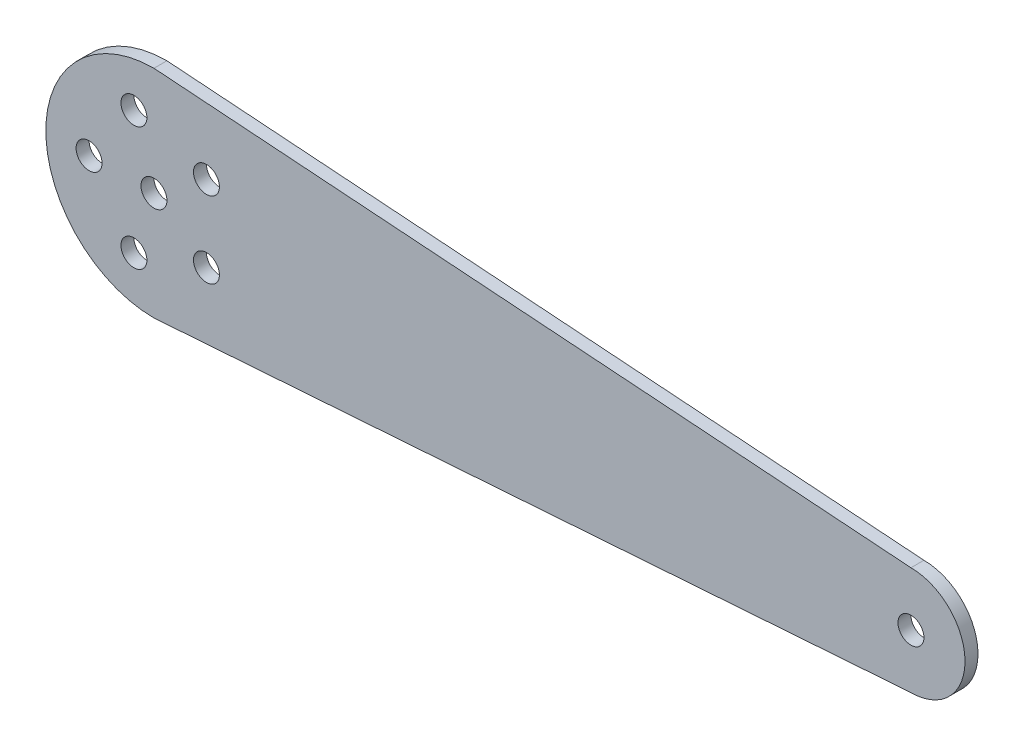
SolidWorks part; units mm, degrees
ref_plane "Front Plane" through (0, 0, 0) normal (0, 0, 1) x (1, 0, 0)
ref_plane "Top Plane" through (0, 0, 0) normal (0, 1, 0) x (1, 0, 0)
ref_plane "Right Plane" through (0, 0, 0) normal (1, 0, 0) x (0, 0, -1)
sketch "Sketch4" plane through (0, 0, 0) normal (0, 0, 1) x (1, 0, 0)
  line L0 (0, 0) -> (175, 0) construction
  line L1 (0, 25) -> (175, 12.5)
  line L2 (0, -25) -> (175, -12.5)
  arc A0 (175, -12.5) -> (175, 12.5) centre (175, 0) ccw
  arc A1 (0, 25) -> (0, -25) centre (0, 0) ccw
  circle A2 centre (0, 0) radius 3
  circle A3 centre (175, 0) radius 3
  circle A4 centre (-15, 0) radius 3
  circle A5 centre (-4.6353, 14.2658) radius 3
  circle A6 centre (12.1353, 8.8168) radius 3
  circle A7 centre (12.1353, -8.8168) radius 3
  circle A8 centre (-4.6353, -14.2658) radius 3
  point P21 (0, 0)
  dimension "D2" = 6
  dimension "D3" = 25
  dimension "D4" = 12.5
  dimension "D5" = 15
  dimension "D7" = 6
  dimension "D8" = 6
  dimension "D1" = 175
  dimension "D6" = 5
extrude "Boss-Extrude1" add sketch "Sketch4" along normal blind 3
